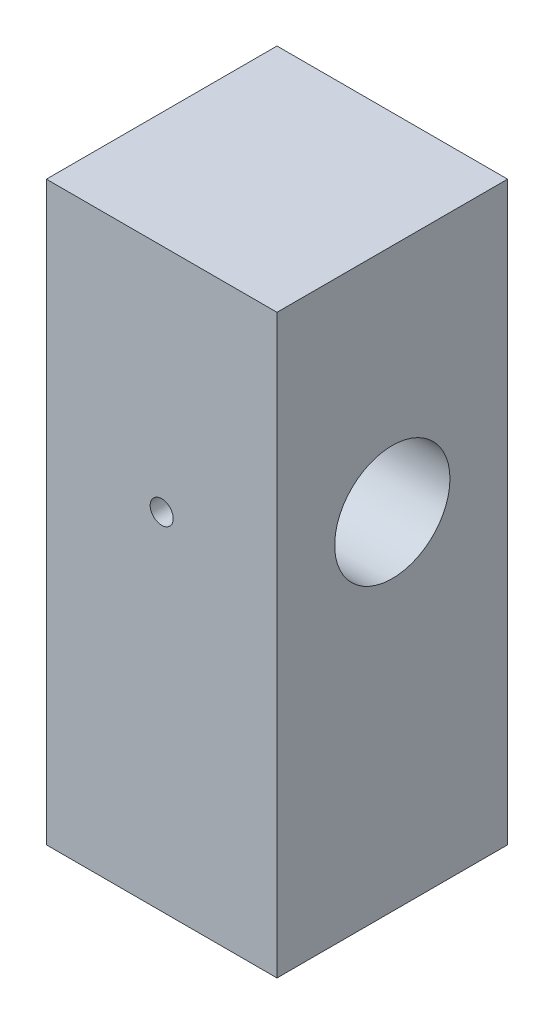
SolidWorks part; units mm, degrees
material "1023 Carbon Steel Sheet (SS)"
ref_plane "Front Plane" through (0, 0, 0) normal (1, 0, 0) x (0, 1, 0)
ref_plane "Top Plane" through (0, 0, 0) normal (0, 0, 1) x (0, 1, 0)
ref_plane "Right Plane" through (0, 0, 0) normal (0, 1, 0) x (-1, 0, 0)
sketch "Sketch1" plane through (0, 0, 0) normal (1, 0, 0) x (0, 1, 0)
  line L1 (-25, -10) -> (25, -10)
  line L2 (-25, -10) -> (-25, 10)
  line L3 (-25, 10) -> (25, 10)
  line L4 (25, -10) -> (25, 10)
  circle A0 centre (5, 0) radius 5
  point P0 (0, 0)
  dimension "D4" = 10
  dimension "D1" = 20
  dimension "D3" = 50
extrude "Boss-Extrude3" add sketch "Sketch1" along normal blind 20
sketch "Sketch2" plane through (0, 0, -10) normal (0, 0, -1) x (1, 0, 0)
  line L0 (10, 25) -> (10, -5)
  line L1 (20, 25) -> (0, 25) construction
  circle A0 centre (10, -5) radius 1
  dimension "D2" = 2
  dimension "D1" = 30
extrude "Cut-Extrude1" cut sketch "Sketch2" against normal through all
